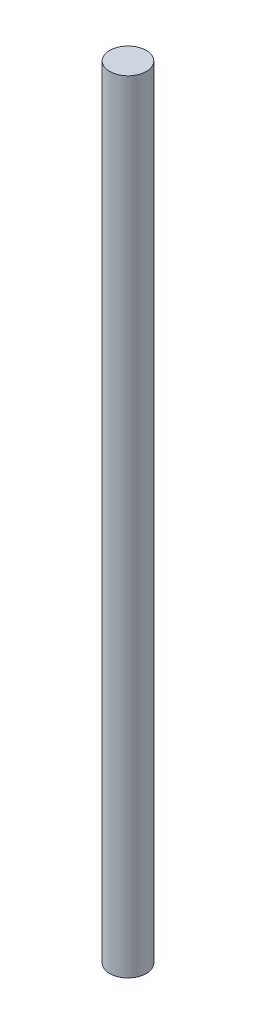
SolidWorks part; units mm, degrees
material "AISI 1020 Steel, Cold Rolled"
ref_plane "Front Plane" through (0, 0, 0) normal (0, 0, 1) x (1, 0, 0)
ref_plane "Top Plane" through (0, 0, 0) normal (0, 1, 0) x (1, 0, 0)
ref_plane "Right Plane" through (0, 0, 0) normal (1, 0, 0) x (0, 0, -1)
sketch "Sketch1" plane through (0, 0, 0) normal (0, 1, 0) x (1, 0, 0)
  circle A0 centre (0, 0) radius 6.35
  dimension "D1" = 12.7
extrude "Boss-Extrude1" add sketch "Sketch1" along normal blind 271.7101
